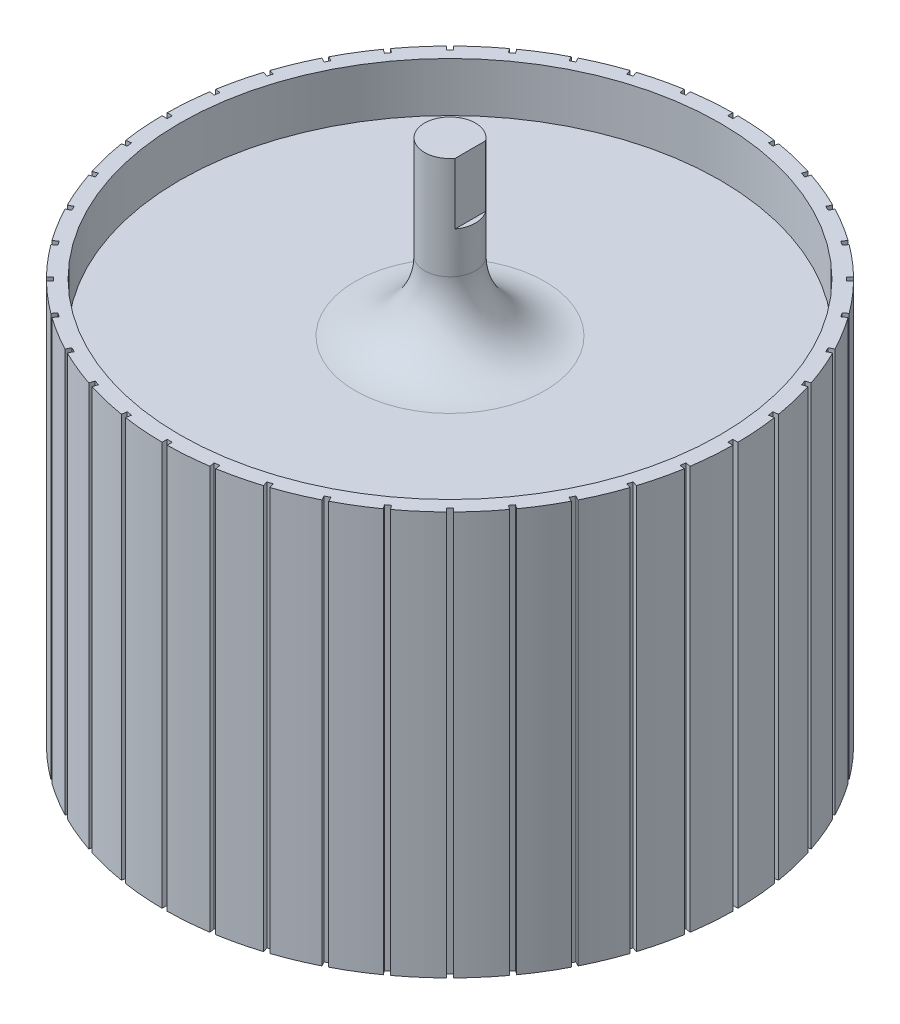
SolidWorks part; units mm, degrees
ref_plane "Front Plane" through (0, 0, 0) normal (0, 0, 1) x (1, 0, 0)
ref_plane "Top Plane" through (0, 0, 0) normal (0, 1, 0) x (1, 0, 0)
ref_plane "Right Plane" through (0, 0, 0) normal (1, 0, 0) x (0, 0, -1)
sketch "Sketch1" plane through (0, 0, 0) normal (0, 1, 0) x (1, 0, 0)
  line L0 (13.123, 87.9297) -> (12.8747, 86.3617)
  line L1 (-0.7937, 88.9) -> (0.7937, 88.9)
  line L2 (-0.7937, 88.9) -> (-0.7937, 87.3125)
  line L3 (-0.7937, 87.3125) -> (0.7937, 87.3125)
  line L4 (0.7937, 88.9) -> (0.7937, 87.3125)
  line L5 (13.123, 87.9297) -> (14.691, 87.6813)
  line L6 (14.691, 87.6813) -> (14.4427, 86.1134)
  line L7 (12.8747, 86.3617) -> (14.4427, 86.1134)
  line L8 (26.7167, 84.7942) -> (26.2261, 83.2844)
  line L9 (26.7167, 84.7942) -> (28.2265, 84.3036)
  line L10 (28.2265, 84.3036) -> (27.7359, 82.7938)
  line L11 (26.2261, 83.2844) -> (27.7359, 82.7938)
  line L12 (39.6525, 79.5708) -> (38.9318, 78.1564)
  line L13 (39.6525, 79.5708) -> (41.067, 78.8501)
  line L14 (41.067, 78.8501) -> (40.3463, 77.4357)
  line L15 (38.9318, 78.1564) -> (40.3463, 77.4357)
  line L16 (51.612, 72.3882) -> (50.6788, 71.1039)
  line L17 (51.612, 72.3882) -> (52.8963, 71.4551)
  line L18 (52.8963, 71.4551) -> (51.9632, 70.1707)
  line L19 (50.6788, 71.1039) -> (51.9632, 70.1707)
  line L20 (62.3005, 63.4231) -> (61.178, 62.3005)
  line L21 (62.3005, 63.4231) -> (63.4231, 62.3005)
  line L22 (63.4231, 62.3005) -> (62.3005, 61.178)
  line L23 (61.178, 62.3005) -> (62.3005, 61.178)
  line L24 (71.4551, 52.8963) -> (70.1707, 51.9632)
  line L25 (71.4551, 52.8963) -> (72.3882, 51.612)
  line L26 (72.3882, 51.612) -> (71.1039, 50.6788)
  line L27 (70.1707, 51.9632) -> (71.1039, 50.6788)
  line L28 (78.8501, 41.067) -> (77.4357, 40.3463)
  line L29 (78.8501, 41.067) -> (79.5708, 39.6525)
  line L30 (79.5708, 39.6525) -> (78.1564, 38.9318)
  line L31 (77.4357, 40.3463) -> (78.1564, 38.9318)
  line L32 (84.3036, 28.2265) -> (82.7938, 27.7359)
  line L33 (84.3036, 28.2265) -> (84.7942, 26.7167)
  line L34 (84.7942, 26.7167) -> (83.2844, 26.2261)
  line L35 (82.7938, 27.7359) -> (83.2844, 26.2261)
  line L36 (87.6813, 14.691) -> (86.1134, 14.4427)
  line L37 (87.6813, 14.691) -> (87.9297, 13.123)
  line L38 (87.9297, 13.123) -> (86.3617, 12.8747)
  line L39 (86.1134, 14.4427) -> (86.3617, 12.8747)
  line L40 (88.9, 0.7938) -> (87.3125, 0.7938)
  line L41 (88.9, 0.7938) -> (88.9, -0.7937)
  line L42 (88.9, -0.7937) -> (87.3125, -0.7937)
  line L43 (87.3125, 0.7938) -> (87.3125, -0.7937)
  line L44 (87.9297, -13.123) -> (86.3617, -12.8747)
  line L45 (87.9297, -13.123) -> (87.6813, -14.691)
  line L46 (87.6813, -14.691) -> (86.1134, -14.4427)
  line L47 (86.3617, -12.8747) -> (86.1134, -14.4427)
  line L48 (84.7942, -26.7167) -> (83.2844, -26.2261)
  line L49 (84.7942, -26.7167) -> (84.3036, -28.2265)
  line L50 (84.3036, -28.2265) -> (82.7938, -27.7359)
  line L51 (83.2844, -26.2261) -> (82.7938, -27.7359)
  line L52 (79.5708, -39.6525) -> (78.1564, -38.9318)
  line L53 (79.5708, -39.6525) -> (78.8501, -41.067)
  line L54 (78.8501, -41.067) -> (77.4357, -40.3463)
  line L55 (78.1564, -38.9318) -> (77.4357, -40.3463)
  line L56 (72.3882, -51.612) -> (71.1039, -50.6788)
  line L57 (72.3882, -51.612) -> (71.4551, -52.8963)
  line L58 (71.4551, -52.8963) -> (70.1707, -51.9632)
  line L59 (71.1039, -50.6788) -> (70.1707, -51.9632)
  line L60 (63.4231, -62.3005) -> (62.3005, -61.178)
  line L61 (63.4231, -62.3005) -> (62.3005, -63.4231)
  line L62 (62.3005, -63.4231) -> (61.178, -62.3005)
  line L63 (62.3005, -61.178) -> (61.178, -62.3005)
  line L64 (52.8963, -71.4551) -> (51.9632, -70.1707)
  line L65 (52.8963, -71.4551) -> (51.612, -72.3882)
  line L66 (51.612, -72.3882) -> (50.6788, -71.1039)
  line L67 (51.9632, -70.1707) -> (50.6788, -71.1039)
  line L68 (41.067, -78.8501) -> (40.3463, -77.4357)
  line L69 (41.067, -78.8501) -> (39.6525, -79.5708)
  line L70 (39.6525, -79.5708) -> (38.9318, -78.1564)
  line L71 (40.3463, -77.4357) -> (38.9318, -78.1564)
  line L72 (28.2265, -84.3036) -> (27.7359, -82.7938)
  line L73 (28.2265, -84.3036) -> (26.7167, -84.7942)
  line L74 (26.7167, -84.7942) -> (26.2261, -83.2844)
  line L75 (27.7359, -82.7938) -> (26.2261, -83.2844)
  line L76 (14.691, -87.6813) -> (14.4427, -86.1134)
  line L77 (14.691, -87.6813) -> (13.123, -87.9297)
  line L78 (13.123, -87.9297) -> (12.8747, -86.3617)
  line L79 (14.4427, -86.1134) -> (12.8747, -86.3617)
  line L80 (0.7938, -88.9) -> (0.7938, -87.3125)
  line L81 (0.7938, -88.9) -> (-0.7937, -88.9)
  line L82 (-0.7937, -88.9) -> (-0.7937, -87.3125)
  line L83 (0.7938, -87.3125) -> (-0.7937, -87.3125)
  line L84 (-13.123, -87.9297) -> (-12.8747, -86.3617)
  line L85 (-13.123, -87.9297) -> (-14.691, -87.6813)
  line L86 (-14.691, -87.6813) -> (-14.4427, -86.1134)
  line L87 (-12.8747, -86.3617) -> (-14.4427, -86.1134)
  line L88 (-26.7167, -84.7942) -> (-26.2261, -83.2844)
  line L89 (-26.7167, -84.7942) -> (-28.2265, -84.3036)
  line L90 (-28.2265, -84.3036) -> (-27.7359, -82.7938)
  line L91 (-26.2261, -83.2844) -> (-27.7359, -82.7938)
  line L92 (-39.6525, -79.5708) -> (-38.9318, -78.1564)
  line L93 (-39.6525, -79.5708) -> (-41.067, -78.8501)
  line L94 (-41.067, -78.8501) -> (-40.3463, -77.4357)
  line L95 (-38.9318, -78.1564) -> (-40.3463, -77.4357)
  line L96 (-51.612, -72.3882) -> (-50.6788, -71.1039)
  line L97 (-51.612, -72.3882) -> (-52.8963, -71.4551)
  line L98 (-52.8963, -71.4551) -> (-51.9632, -70.1707)
  line L99 (-50.6788, -71.1039) -> (-51.9632, -70.1707)
  line L100 (-62.3005, -63.4231) -> (-61.178, -62.3005)
  line L101 (-62.3005, -63.4231) -> (-63.4231, -62.3005)
  line L102 (-63.4231, -62.3005) -> (-62.3005, -61.178)
  line L103 (-61.178, -62.3005) -> (-62.3005, -61.178)
  line L104 (-71.4551, -52.8963) -> (-70.1707, -51.9632)
  line L105 (-71.4551, -52.8963) -> (-72.3882, -51.612)
  line L106 (-72.3882, -51.612) -> (-71.1039, -50.6788)
  line L107 (-70.1707, -51.9632) -> (-71.1039, -50.6788)
  line L108 (-78.8501, -41.067) -> (-77.4357, -40.3463)
  line L109 (-78.8501, -41.067) -> (-79.5708, -39.6525)
  line L110 (-79.5708, -39.6525) -> (-78.1564, -38.9318)
  line L111 (-77.4357, -40.3463) -> (-78.1564, -38.9318)
  line L112 (-84.3036, -28.2265) -> (-82.7938, -27.7359)
  line L113 (-84.3036, -28.2265) -> (-84.7942, -26.7167)
  line L114 (-84.7942, -26.7167) -> (-83.2844, -26.2261)
  line L115 (-82.7938, -27.7359) -> (-83.2844, -26.2261)
  line L116 (-87.6813, -14.691) -> (-86.1134, -14.4427)
  line L117 (-87.6813, -14.691) -> (-87.9297, -13.123)
  line L118 (-87.9297, -13.123) -> (-86.3617, -12.8747)
  line L119 (-86.1134, -14.4427) -> (-86.3617, -12.8747)
  line L120 (-88.9, -0.7938) -> (-87.3125, -0.7938)
  line L121 (-88.9, -0.7938) -> (-88.9, 0.7937)
  line L122 (-88.9, 0.7937) -> (-87.3125, 0.7937)
  line L123 (-87.3125, -0.7938) -> (-87.3125, 0.7937)
  line L124 (-87.9297, 13.123) -> (-86.3617, 12.8747)
  line L125 (-87.9297, 13.123) -> (-87.6813, 14.691)
  line L126 (-87.6813, 14.691) -> (-86.1134, 14.4427)
  line L127 (-86.3617, 12.8747) -> (-86.1134, 14.4427)
  line L128 (-84.7942, 26.7167) -> (-83.2844, 26.2261)
  line L129 (-84.7942, 26.7167) -> (-84.3036, 28.2265)
  line L130 (-84.3036, 28.2265) -> (-82.7938, 27.7359)
  line L131 (-83.2844, 26.2261) -> (-82.7938, 27.7359)
  line L132 (-79.5708, 39.6525) -> (-78.1564, 38.9318)
  line L133 (-79.5708, 39.6525) -> (-78.8501, 41.067)
  line L134 (-78.8501, 41.067) -> (-77.4357, 40.3463)
  line L135 (-78.1564, 38.9318) -> (-77.4357, 40.3463)
  line L136 (-72.3882, 51.612) -> (-71.1039, 50.6788)
  line L137 (-72.3882, 51.612) -> (-71.4551, 52.8963)
  line L138 (-71.4551, 52.8963) -> (-70.1707, 51.9632)
  line L139 (-71.1039, 50.6788) -> (-70.1707, 51.9632)
  line L140 (-63.4231, 62.3005) -> (-62.3005, 61.178)
  line L141 (-63.4231, 62.3005) -> (-62.3005, 63.4231)
  line L142 (-62.3005, 63.4231) -> (-61.178, 62.3005)
  line L143 (-62.3005, 61.178) -> (-61.178, 62.3005)
  line L144 (-52.8963, 71.4551) -> (-51.9632, 70.1707)
  line L145 (-52.8963, 71.4551) -> (-51.612, 72.3882)
  line L146 (-51.612, 72.3882) -> (-50.6788, 71.1039)
  line L147 (-51.9632, 70.1707) -> (-50.6788, 71.1039)
  line L148 (-41.067, 78.8501) -> (-40.3463, 77.4357)
  line L149 (-41.067, 78.8501) -> (-39.6525, 79.5708)
  line L150 (-39.6525, 79.5708) -> (-38.9318, 78.1564)
  line L151 (-40.3463, 77.4357) -> (-38.9318, 78.1564)
  line L152 (-28.2265, 84.3036) -> (-27.7359, 82.7938)
  line L153 (-28.2265, 84.3036) -> (-26.7167, 84.7942)
  line L154 (-26.7167, 84.7942) -> (-26.2261, 83.2844)
  line L155 (-27.7359, 82.7938) -> (-26.2261, 83.2844)
  line L156 (-14.691, 87.6813) -> (-14.4427, 86.1134)
  line L157 (-14.691, 87.6813) -> (-13.123, 87.9297)
  line L158 (-13.123, 87.9297) -> (-12.8747, 86.3617)
  line L159 (-14.4427, 86.1134) -> (-12.8747, 86.3617)
  circle A0 centre (0, 0) radius 88.9
  circle A1 centre (0, 0) radius 84.1375
  point P10 (0, 88.9)
  point P88 (0, 0)
  dimension "D1" = 177.8
  dimension "D2" = 4.7625
  dimension "D3" = 1.5875
  dimension "D4" = 1.5875
  dimension "D5" = 40
extrude "Boss-Extrude1" add sketch "Sketch1" along normal mid plane 125.73 contours L40 A0 L38 L39 L36 L34 L35 L32 L30 L31 L28 L26 L27 L24 L22 L23 L20 L18 L19 L16 L14 L15 L12 L10 L11 L8 L6 L7 L0 L4 L3 L2 L78 L79 L76 L74 L75 L72 L70
sketch "Sketch2" plane through (0, 0, 0) normal (0, 0, 1) x (1, 0, 0)
  line L0 (0, 100.965) -> (0, 41.115)
  line L1 (0, 41.115) -> (-84.1375, 41.115)
  line L2 (-84.1375, 41.115) -> (-84.1375, 47.465)
  line L3 (-84.1375, 47.465) -> (-7.9375, 47.465)
  line L4 (-7.9375, 47.465) -> (-7.9375, 100.965)
  line L5 (-7.9375, 100.965) -> (0, 100.965)
  line L6 (87.6778, 62.865) -> (84.7908, 62.865) construction
  line L7 (88.8965, 62.865) -> (87.9262, 62.865) construction
  dimension "D1" = 6.35
  dimension "D2" = 15.4
  dimension "D3" = 38.1
  dimension "D4" = 7.9375
revolve "Revolve1" add sketch "Sketch2" angle 360 about L0
fillet "Fillet1" radius 3.175 1 edges at (84.1375, 41.115, 0)
mirror "Mirror1" about plane through (0, 0, 0) normal (0, 1, 0) of "Fillet1", "Revolve1"
fillet "Fillet2" radius 21.59 2 edges at (-7.9375, -47.465, 0) (-7.9375, 47.465, 0)
sketch "Sketch3" plane through (0, 62.865, 0) normal (0, 1, 0) x (1, 0, 0)
  line L0 (-79.6925, 0) -> (-87.3125, 0) construction
  line L1 (-87.3125, -0.7938) -> (-87.3125, 0.7937) construction
  line L2 (-84.0512, 3.809) -> (-84.1375, 0)
  line L3 (-83.7565, 7.9978) -> (-79.3316, 7.5753)
  line L4 (-84.1375, 0) -> (-79.6925, 0)
  line L5 (-84.0512, 3.809) -> (-79.3301, 7.5917)
  line L6 (-83.3086, 11.7814) -> (-78.2492, 15.0982)
  line L7 (-83.3086, 11.7814) -> (-83.7565, 7.9978)
  line L8 (-82.617, 15.9231) -> (-78.2524, 15.0819)
  line L9 (-81.8115, 19.647) -> (-76.4597, 22.4679)
  line L10 (-81.8115, 19.647) -> (-82.617, 15.9231)
  line L11 (-80.7293, 23.7043) -> (-76.4644, 22.452)
  line L12 (-79.5734, 27.3347) -> (-73.9778, 29.6341)
  line L13 (-79.5734, 27.3347) -> (-80.7293, 23.7043)
  line L14 (-78.1106, 31.2707) -> (-73.984, 29.6187)
  line L15 (-76.6148, 34.7749) -> (-70.8259, 36.5319)
  line L16 (-76.6148, 34.7749) -> (-78.1106, 31.2707)
  line L17 (-74.7844, 38.554) -> (-70.8335, 36.5172)
  line L18 (-72.9623, 41.9001) -> (-67.0326, 43.099)
  line L19 (-72.9623, 41.9001) -> (-74.7844, 38.554)
  line L20 (-70.781, 45.4882) -> (-67.0416, 43.085)
  line L21 (-68.6491, 48.6459) -> (-62.6323, 49.2757)
  line L22 (-68.6491, 48.6459) -> (-70.781, 45.4882)
  line L23 (-66.1365, 52.0104) -> (-62.6425, 49.2626)
  line L24 (-63.7142, 54.9511) -> (-57.6647, 55.0061)
  line L25 (-63.7142, 54.9511) -> (-66.1365, 52.0104)
  line L26 (-60.8932, 58.0615) -> (-57.6762, 54.9941)
  line L27 (-58.2022, 60.7587) -> (-52.175, 60.2384)
  line L28 (-58.2022, 60.7587) -> (-60.8932, 58.0615)
  line L29 (-55.0983, 63.5869) -> (-52.1875, 60.2276)
  line L30 (-52.1632, 66.0161) -> (-46.2127, 64.9252)
  line L31 (-52.1632, 66.0161) -> (-55.0983, 63.5869)
  line L32 (-48.8045, 68.5364) -> (-46.2262, 64.9156)
  line L33 (-45.6518, 70.6756) -> (-39.8319, 69.024)
  line L34 (-45.6518, 70.6756) -> (-48.8045, 68.5364)
  line L35 (-42.0687, 72.8652) -> (-39.8462, 69.0157)
  line L36 (-38.7269, 74.695) -> (-33.0904, 72.4977)
  line L37 (-38.7269, 74.695) -> (-42.0687, 72.8652)
  line L38 (-34.952, 76.5342) -> (-33.1055, 72.4908)
  line L39 (-31.4513, 78.038) -> (-26.0492, 75.3149)
  line L40 (-31.4513, 78.038) -> (-34.952, 76.5342)
  line L41 (-27.5187, 79.51) -> (-26.0649, 75.3095)
  line L42 (-23.8909, 80.6743) -> (-18.7721, 77.45)
  line L43 (-23.8909, 80.6743) -> (-27.5187, 79.51)
  line L44 (-19.8362, 81.7658) -> (-18.7882, 77.4461)
  line L45 (-16.1142, 82.58) -> (-11.325, 78.8837)
  line L46 (-16.1142, 82.58) -> (-19.8362, 81.7658)
  line L47 (-11.974, 83.2811) -> (-11.3414, 78.8813)
  line L48 (-8.1915, 83.7378) -> (-3.7754, 79.603)
  line L49 (-8.1915, 83.7378) -> (-11.974, 83.2811)
  line L50 (-4.0034, 84.0422) -> (-3.7919, 79.6022)
  line L51 (-0.1946, 84.1373) -> (3.8085, 79.6014)
  line L52 (-0.1946, 84.1373) -> (-4.0034, 84.0422)
  line L53 (4.0034, 84.0422) -> (3.7919, 79.6022)
  line L54 (7.804, 83.7748) -> (11.3578, 78.879)
  line L55 (7.804, 83.7748) -> (4.0034, 84.0422)
  line L56 (11.974, 83.2811) -> (11.3414, 78.8813)
  line L57 (15.732, 82.6536) -> (18.8043, 77.4422)
  line L58 (15.732, 82.6536) -> (11.974, 83.2811)
  line L59 (19.8362, 81.7658) -> (18.7882, 77.4461)
  line L60 (23.5175, 80.784) -> (26.0805, 75.3041)
  line L61 (23.5175, 80.784) -> (19.8362, 81.7658)
  line L62 (27.5187, 79.51) -> (26.0649, 75.3095)
  line L63 (31.09, 78.1827) -> (33.1205, 72.484)
  line L64 (31.09, 78.1827) -> (27.5187, 79.51)
  line L65 (34.952, 76.5342) -> (33.1055, 72.4908)
  line L66 (38.381, 74.8734) -> (39.8606, 69.0074)
  line L67 (38.381, 74.8734) -> (34.952, 76.5342)
  line L68 (42.0688, 72.8652) -> (39.8463, 69.0157)
  line L69 (45.3243, 70.886) -> (46.2397, 64.906)
  line L70 (45.3243, 70.886) -> (42.0688, 72.8652)
  line L71 (48.8045, 68.5364) -> (46.2262, 64.9156)
  line L72 (51.8572, 66.2567) -> (52.2, 60.2167)
  line L73 (51.8572, 66.2567) -> (48.8045, 68.5364)
  line L74 (55.0983, 63.5869) -> (52.1875, 60.2276)
  line L75 (57.9205, 61.0273) -> (57.6876, 54.9821)
  line L76 (57.9205, 61.0273) -> (55.0983, 63.5869)
  line L77 (60.8932, 58.0615) -> (57.6762, 54.9941)
  line L78 (63.4593, 55.2453) -> (62.6528, 49.2496)
  line L79 (63.4593, 55.2453) -> (60.8932, 58.0615)
  line L80 (66.1365, 52.0104) -> (62.6425, 49.2626)
  line L81 (68.4233, 48.9629) -> (67.0506, 43.0711)
  line L82 (68.4233, 48.9629) -> (66.1365, 52.0104)
  line L83 (70.781, 45.4882) -> (67.0416, 43.085)
  line L84 (72.7677, 42.2372) -> (70.8411, 36.5025)
  line L85 (72.7677, 42.2372) -> (70.781, 45.4882)
  line L86 (74.7844, 38.554) -> (70.8335, 36.5172)
  line L87 (76.4531, 35.1289) -> (73.9901, 29.6033)
  line L88 (76.4531, 35.1289) -> (74.7844, 38.554)
  line L89 (78.1106, 31.2707) -> (73.984, 29.6187)
  line L90 (79.4461, 27.7025) -> (76.4691, 22.4361)
  line L91 (79.4461, 27.7025) -> (78.1106, 31.2707)
  line L92 (80.7293, 23.7043) -> (76.4644, 22.452)
  line L93 (81.7197, 20.0252) -> (78.2555, 15.0656)
  line L94 (81.7197, 20.0252) -> (80.7293, 23.7043)
  line L95 (82.617, 15.9231) -> (78.2524, 15.0819)
  line L96 (83.2532, 12.1666) -> (79.3332, 7.5588)
  line L97 (83.2532, 12.1666) -> (82.617, 15.9231)
  line L98 (83.7565, 7.9978) -> (79.3316, 7.5753)
  line L99 (84.0327, 4.1978) -> (79.6925, -0.0166)
  line L100 (84.0327, 4.1978) -> (83.7565, 7.9978)
  line L101 (84.1375, 0) -> (79.6925, 0)
  line L102 (84.0512, -3.809) -> (79.3301, -7.5917)
  line L103 (84.0512, -3.809) -> (84.1375, 0)
  line L104 (83.7565, -7.9978) -> (79.3316, -7.5753)
  line L105 (83.3086, -11.7814) -> (78.2492, -15.0982)
  line L106 (83.3086, -11.7814) -> (83.7565, -7.9978)
  line L107 (82.617, -15.9231) -> (78.2524, -15.0819)
  line L108 (81.8115, -19.647) -> (76.4597, -22.4679)
  line L109 (81.8115, -19.647) -> (82.617, -15.9231)
  line L110 (80.7293, -23.7043) -> (76.4644, -22.452)
  line L111 (79.5734, -27.3347) -> (73.9778, -29.6341)
  line L112 (79.5734, -27.3347) -> (80.7293, -23.7043)
  line L113 (78.1106, -31.2707) -> (73.984, -29.6187)
  line L114 (76.6148, -34.7749) -> (70.8259, -36.5319)
  line L115 (76.6148, -34.7749) -> (78.1106, -31.2707)
  line L116 (74.7844, -38.554) -> (70.8335, -36.5172)
  line L117 (72.9623, -41.9001) -> (67.0326, -43.099)
  line L118 (72.9623, -41.9001) -> (74.7844, -38.554)
  line L119 (70.781, -45.4882) -> (67.0416, -43.085)
  line L120 (68.6491, -48.6459) -> (62.6323, -49.2757)
  line L121 (68.6491, -48.6459) -> (70.781, -45.4882)
  line L122 (66.1365, -52.0104) -> (62.6425, -49.2626)
  line L123 (63.7142, -54.9511) -> (57.6647, -55.0061)
  line L124 (63.7142, -54.9511) -> (66.1365, -52.0104)
  line L125 (60.8932, -58.0615) -> (57.6762, -54.9941)
  line L126 (58.2022, -60.7587) -> (52.175, -60.2384)
  line L127 (58.2022, -60.7587) -> (60.8932, -58.0615)
  line L128 (55.0983, -63.5869) -> (52.1875, -60.2276)
  line L129 (52.1632, -66.0161) -> (46.2127, -64.9252)
  line L130 (52.1632, -66.0161) -> (55.0983, -63.5869)
  line L131 (48.8045, -68.5364) -> (46.2262, -64.9156)
  line L132 (45.6518, -70.6756) -> (39.8319, -69.024)
  line L133 (45.6518, -70.6756) -> (48.8045, -68.5364)
  line L134 (42.0687, -72.8652) -> (39.8462, -69.0157)
  line L135 (38.7269, -74.695) -> (33.0904, -72.4977)
  line L136 (38.7269, -74.695) -> (42.0687, -72.8652)
  line L137 (34.952, -76.5342) -> (33.1055, -72.4908)
  line L138 (31.4513, -78.038) -> (26.0492, -75.3149)
  line L139 (31.4513, -78.038) -> (34.952, -76.5342)
  line L140 (27.5187, -79.51) -> (26.0649, -75.3095)
  line L141 (23.8909, -80.6743) -> (18.7721, -77.45)
  line L142 (23.8909, -80.6743) -> (27.5187, -79.51)
  line L143 (19.8362, -81.7658) -> (18.7882, -77.4461)
  line L144 (16.1142, -82.58) -> (11.325, -78.8837)
  line L145 (16.1142, -82.58) -> (19.8362, -81.7658)
  line L146 (11.974, -83.2811) -> (11.3414, -78.8813)
  line L147 (8.1915, -83.7378) -> (3.7754, -79.603)
  line L148 (8.1915, -83.7378) -> (11.974, -83.2811)
  line L149 (4.0034, -84.0422) -> (3.7919, -79.6022)
  line L150 (0.1946, -84.1373) -> (-3.8085, -79.6014)
  line L151 (0.1946, -84.1373) -> (4.0034, -84.0422)
  line L152 (-4.0034, -84.0422) -> (-3.7919, -79.6022)
  line L153 (-7.804, -83.7748) -> (-11.3578, -78.879)
  line L154 (-7.804, -83.7748) -> (-4.0034, -84.0422)
  line L155 (-11.974, -83.2811) -> (-11.3414, -78.8813)
  line L156 (-15.732, -82.6536) -> (-18.8043, -77.4422)
  line L157 (-15.732, -82.6536) -> (-11.974, -83.2811)
  line L158 (-19.8362, -81.7658) -> (-18.7882, -77.4461)
  line L159 (-23.5175, -80.784) -> (-26.0805, -75.3041)
  line L160 (-23.5175, -80.784) -> (-19.8362, -81.7658)
  line L161 (-27.5187, -79.51) -> (-26.0649, -75.3095)
  line L162 (-31.09, -78.1827) -> (-33.1205, -72.484)
  line L163 (-31.09, -78.1827) -> (-27.5187, -79.51)
  line L164 (-34.952, -76.5342) -> (-33.1055, -72.4908)
  line L165 (-38.381, -74.8734) -> (-39.8606, -69.0074)
  line L166 (-38.381, -74.8734) -> (-34.952, -76.5342)
  line L167 (-42.0688, -72.8652) -> (-39.8463, -69.0157)
  line L168 (-45.3243, -70.886) -> (-46.2397, -64.906)
  line L169 (-45.3243, -70.886) -> (-42.0688, -72.8652)
  line L170 (-48.8045, -68.5364) -> (-46.2262, -64.9156)
  line L171 (-51.8572, -66.2567) -> (-52.2, -60.2167)
  line L172 (-51.8572, -66.2567) -> (-48.8045, -68.5364)
  line L173 (-55.0983, -63.5869) -> (-52.1875, -60.2276)
  line L174 (-57.9205, -61.0273) -> (-57.6876, -54.9821)
  line L175 (-57.9205, -61.0273) -> (-55.0983, -63.5869)
  line L176 (-60.8932, -58.0615) -> (-57.6762, -54.9941)
  line L177 (-63.4593, -55.2453) -> (-62.6528, -49.2496)
  line L178 (-63.4593, -55.2453) -> (-60.8932, -58.0615)
  line L179 (-66.1365, -52.0104) -> (-62.6425, -49.2626)
  line L180 (-68.4233, -48.9629) -> (-67.0506, -43.0711)
  line L181 (-68.4233, -48.9629) -> (-66.1365, -52.0104)
  line L182 (-70.781, -45.4882) -> (-67.0416, -43.085)
  line L183 (-72.7677, -42.2372) -> (-70.8411, -36.5025)
  line L184 (-72.7677, -42.2372) -> (-70.781, -45.4882)
  line L185 (-74.7844, -38.554) -> (-70.8335, -36.5172)
  line L186 (-76.4531, -35.1289) -> (-73.9901, -29.6033)
  line L187 (-76.4531, -35.1289) -> (-74.7844, -38.554)
  line L188 (-78.1106, -31.2707) -> (-73.984, -29.6187)
  line L189 (-79.4461, -27.7025) -> (-76.4691, -22.4361)
  line L190 (-79.4461, -27.7025) -> (-78.1106, -31.2707)
  line L191 (-80.7293, -23.7043) -> (-76.4644, -22.452)
  line L192 (-81.7197, -20.0252) -> (-78.2555, -15.0656)
  line L193 (-81.7197, -20.0252) -> (-80.7293, -23.7043)
  line L194 (-82.617, -15.9231) -> (-78.2524, -15.0819)
  line L195 (-83.2532, -12.1666) -> (-79.3332, -7.5588)
  line L196 (-83.2532, -12.1666) -> (-82.617, -15.9231)
  line L197 (-83.7565, -7.9978) -> (-79.3316, -7.5753)
  line L198 (-84.0327, -4.1978) -> (-79.6925, 0.0166)
  line L199 (-84.0327, -4.1978) -> (-83.7565, -7.9978)
  circle A3 centre (0, 0) radius 84.1375
  circle A4 centre (0, 0) radius 79.6925
  circle A6 centre (0, 0) radius 84.1375 construction
  point P233 (0, 0)
  dimension "D1" = 4.445
  dimension "D2" = 3.81
  dimension "D3" = 50
  dimension "D4" = 66
extrude "Inner Teeth" [suppressed] add sketch "Sketch3" against normal up to surface (25.4 mm away)
sketch "Sketch4" plane through (0, 100.965, 0) normal (0, 1, 0) x (1, 0, 0)
  line L0 (6.35, 4.7625) -> (6.35, -4.7625)
  arc A0 (6.35, -4.7625) -> (6.35, 4.7625) centre (0, 0) ccw
  circle A1 centre (0, 0) radius 7.9375 construction
  dimension "D1" = 9.525
extrude "Cut-Extrude1" cut sketch "Sketch4" along a picked direction on the side against the normal blind 19.05
mirror "Mirror2" about plane through (0, 0, 0) normal (0, 1, 0) of "Cut-Extrude1"
